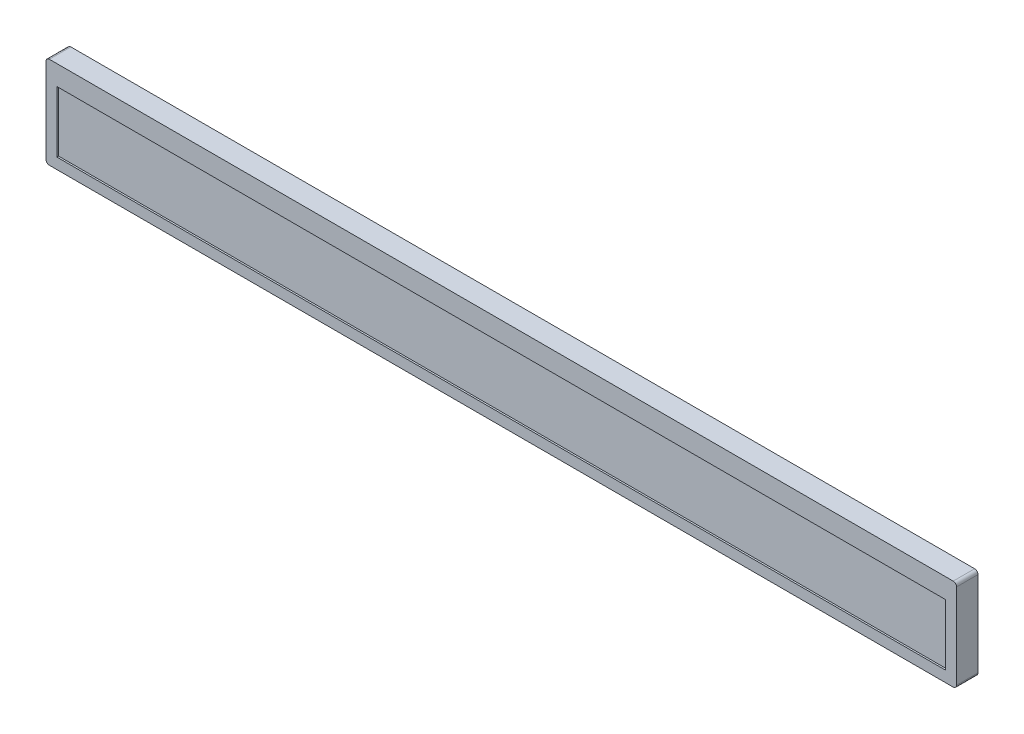
SolidWorks part; units mm, degrees
ref_plane "Front Plane" through (0, 0, 0) normal (0, 0, 1) x (1, 0, 0)
ref_plane "Top Plane" through (0, 0, 0) normal (0, 1, 0) x (1, 0, 0)
ref_plane "Right Plane" through (0, 0, 0) normal (1, 0, 0) x (0, 0, -1)
sketch "Sketch1" plane through (0, 0, 0) normal (0, 0, 1) x (1, 0, 0)
  line L1 (-269.21, 27.35) -> (269.21, 27.35)
  line L2 (-271.21, 25.35) -> (-271.21, -25.35)
  line L3 (-269.21, -27.35) -> (269.21, -27.35)
  line L4 (271.21, 25.35) -> (271.21, -25.35)
  line L5 (-271.21, 27.35) -> (271.21, -27.35) construction
  line L6 (-271.21, -27.35) -> (271.21, 27.35) construction
  arc A0 (269.21, 27.35) -> (271.21, 25.35) centre (269.21, 25.35) cw
  arc A1 (269.21, -27.35) -> (271.21, -25.35) centre (269.21, -25.35) ccw
  arc A2 (-271.21, -25.35) -> (-269.21, -27.35) centre (-269.21, -25.35) ccw
  arc A3 (-269.21, 27.35) -> (-271.21, 25.35) centre (-269.21, 25.35) ccw
  point P0 (0, 0)
  dimension "D1" = 2
  dimension "D2" = 542.42
  dimension "D3" = 54.7
extrude "Boss-Extrude1" add sketch "Sketch1" along normal blind 12.77
sketch "Sketch2" plane through (0, 0, 12.77) normal (0, 0, 1) x (1, 0, 0)
  line L0 (264.71, 15.53) -> (264.71, -20.87)
  line L1 (264.71, 15.53) -> (-264.71, 15.53)
  line L2 (0, 15.53) -> (0, -20.87) construction
  line L3 (264.71, -20.87) -> (-264.71, -20.87)
  line L4 (-264.71, 15.53) -> (-264.71, -20.87)
  line L5 (269.21, 27.35) -> (-269.21, 27.35) construction
  dimension "D1" = 529.42
  dimension "D2" = 36.4
  dimension "D3" = 11.82
extrude "Cut-Extrude1" cut sketch "Sketch2" against normal blind 1
sketch "Sketch3" plane through (0, 0, 0) normal (0, 0, -1) x (-1, 0, 0)
  line L0 (-269.21, 27.35) -> (269.21, 27.35) construction
  line L1 (0, 27.35) -> (0, -27.35) construction
  line L2 (269.21, -27.35) -> (-269.21, -27.35) construction
  line L4 (-17.16, -12.47) -> (17.16, -12.47)
  line L5 (-17.16, -12.47) -> (-17.16, -27.35)
  line L6 (-17.16, -27.35) -> (17.16, -27.35)
  line L7 (17.16, -12.47) -> (17.16, -27.35)
  circle A0 centre (-253.41, 4.02) radius 2.5
  circle A1 centre (-253.41, -10.06) radius 2.5
  circle A2 centre (-113, -10.06) radius 2.5
  circle A3 centre (113, -10.06) radius 2.5
  circle A4 centre (253.41, -10.06) radius 2.5
  circle A5 centre (253.41, 4.02) radius 2.5
  point P2 (-253.41, 4.02)
  point P3 (-253.41, -10.06)
  point P4 (-113, -10.06)
  point P26 (0, -12.47)
  dimension "D1" = 5
  dimension "D6" = 5
  dimension "D7" = 5
  dimension "D2" = 14.08
  dimension "D3" = 23.33
  dimension "D4" = 253.41
  dimension "D5" = 113
  dimension "D8" = 14.88
  dimension "D9" = 34.32
extrude "Boss-Extrude2" add sketch "Sketch3" along normal blind 1.25
